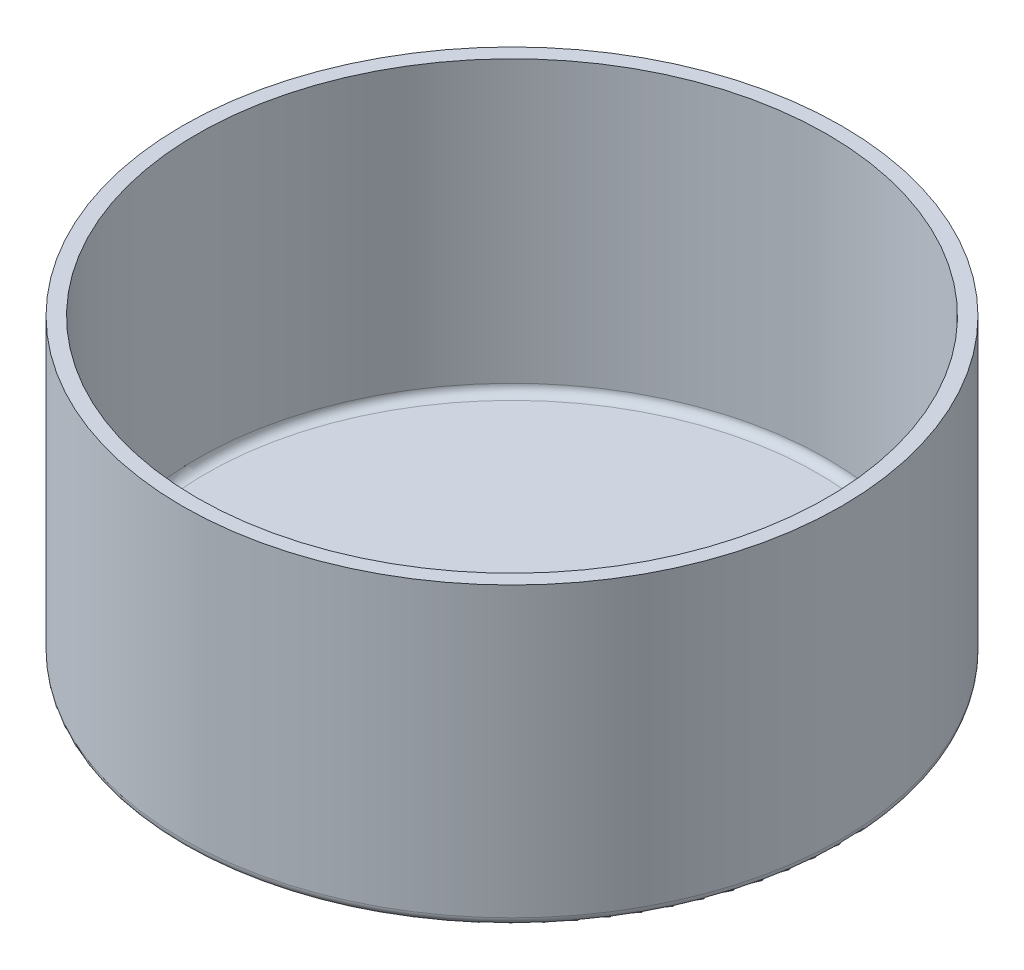
SolidWorks part; units mm, degrees
ref_plane "Alzado" through (0, 0, 0) normal (0, 0, 1) x (1, 0, 0)
ref_plane "Planta" through (0, 0, 0) normal (0, 1, 0) x (1, 0, 0)
ref_plane "Vista lateral" through (0, 0, 0) normal (1, 0, 0) x (0, 0, -1)
sketch "Croquis1" plane through (0, 0, 0) normal (0, 1, 0) x (1, 0, 0)
  circle A0 centre (0, 0) radius 11.375
  dimension "D1" = 22.75
extrude "Saliente-Extruir1" add sketch "Croquis1" along normal blind 0.25
sketch "Croquis2" plane through (0, 0.25, 0) normal (0, 1, 0) x (1, 0, 0)
  circle A0 centre (0, 0) radius 11.375
  circle A1 centre (0, 0) radius 10.875
  dimension "D1" = 22.75
  dimension "D2" = 21.75
extrude "Saliente-Extruir2" add sketch "Croquis2" along normal blind 10
fillet "Redondeo1" radius 0.3 1 edges at (0, 0.25, 10.875)
fillet "Redondeo2" radius 0.3 1 edges at (0, 0, 11.375)
